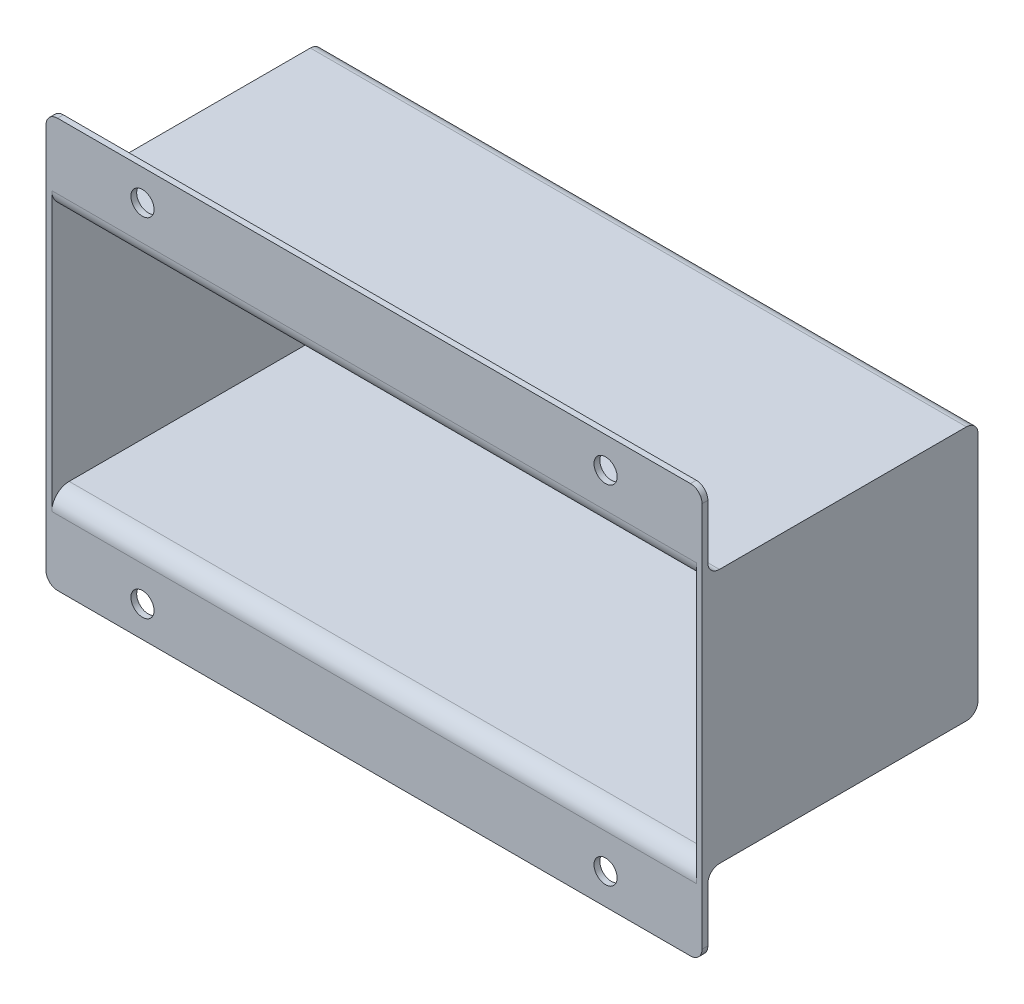
SolidWorks part; units mm, degrees
material "SKD11淬火HRC56-60"
ref_plane "前基準面" through (0, 0, 0) normal (0, 0, 1) x (1, 0, 0)
ref_plane "上基準面" through (0, 0, 0) normal (0, 1, 0) x (1, 0, 0)
ref_plane "右基準面" through (0, 0, 0) normal (1, 0, 0) x (0, 0, -1)
sketch "草图1" plane through (0, 0, 0) normal (0, 0, 1) x (1, 0, 0)
  line L1 (0, 0) -> (170, 0)
  line L2 (0, 0) -> (0, 66)
  line L3 (0, 66) -> (170, 66)
  line L4 (170, 0) -> (170, 66)
  dimension "D1" = 170
  dimension "D2" = 66
extrude "凸台-拉伸1" add sketch "草图1" along normal blind 70
sketch "草图2" plane through (0, 0, 70) normal (0, 0, 1) x (1, 0, 0)
  line L0 (0, 33) -> (170, 33) construction
  line L1 (0, 86) -> (170, 86)
  line L2 (0, 86) -> (0, -20)
  line L3 (0, -20) -> (170, -20)
  line L4 (170, 86) -> (170, -20)
  line L5 (0, 66) -> (0, 0) construction
  line L6 (170, 0) -> (170, 66) construction
  line L7 (0, 0) -> (170, 0) construction
  dimension "D1" = 20
extrude "凸台-拉伸2" add sketch "草图2" along normal blind 5
fillet "圆角1" radius 3 4 edges at (85, 0, 0) (85, 66, 0)
shell "抽壳1" thickness 1.5
sketch "草图3" plane through (168.5, 0, 0) normal (-1, 0, 0) x (0, 0, 1)
  line L1 (71.5, -20) -> (75, -20)
  line L2 (71.5, -20) -> (71.5, 86)
  line L3 (71.5, 86) -> (75, 86)
  line L4 (75, -20) -> (75, 86)
extrude "切除-拉伸1" cut sketch "草图3" against normal blind 5 and the other way through all
sketch "草图4" plane through (0, 0, 0) normal (0, 0, -1) x (-1, 0, 0)
  line L0 (-85, 3) -> (-85, 63) construction
  line L1 (-170, 3) -> (0, 3) construction
  line L2 (0, 63) -> (-170, 63) construction
  circle A0 centre (-135, 33) radius 11
  circle A1 centre (-85, 33) radius 11
  circle A2 centre (-35, 33) radius 11
  dimension "D1" = 50
  dimension "D2" = 22
extrude "切除-拉伸2" cut sketch "草图4" against normal blind 5
sketch "草图5" plane through (0, 0, 71.5) normal (0, 0, 1) x (1, 0, 0)
  line L0 (85, -20) -> (85, 86) construction
  line L1 (0, -20) -> (170, -20) construction
  line L2 (170, 86) -> (0, 86) construction
  line L3 (170, 33) -> (0, 33) construction
  line L4 (170, -20) -> (170, 86) construction
  line L5 (0, 86) -> (0, -20) construction
  circle A0 centre (145, -12) radius 3
  circle A1 centre (25, -12) radius 3
  circle A2 centre (25, 78) radius 3
  circle A3 centre (145, 78) radius 3
  dimension "D1" = 120
  dimension "D2" = 90
  dimension "D3" = 6
extrude "切除-拉伸3" cut sketch "草图5" against normal blind 5
fillet "圆角2" radius 3 4 edges at (170, 86, 70.75) (0, 86, 70.75) (0, -20, 70.75) (170, -20, 70.75)
